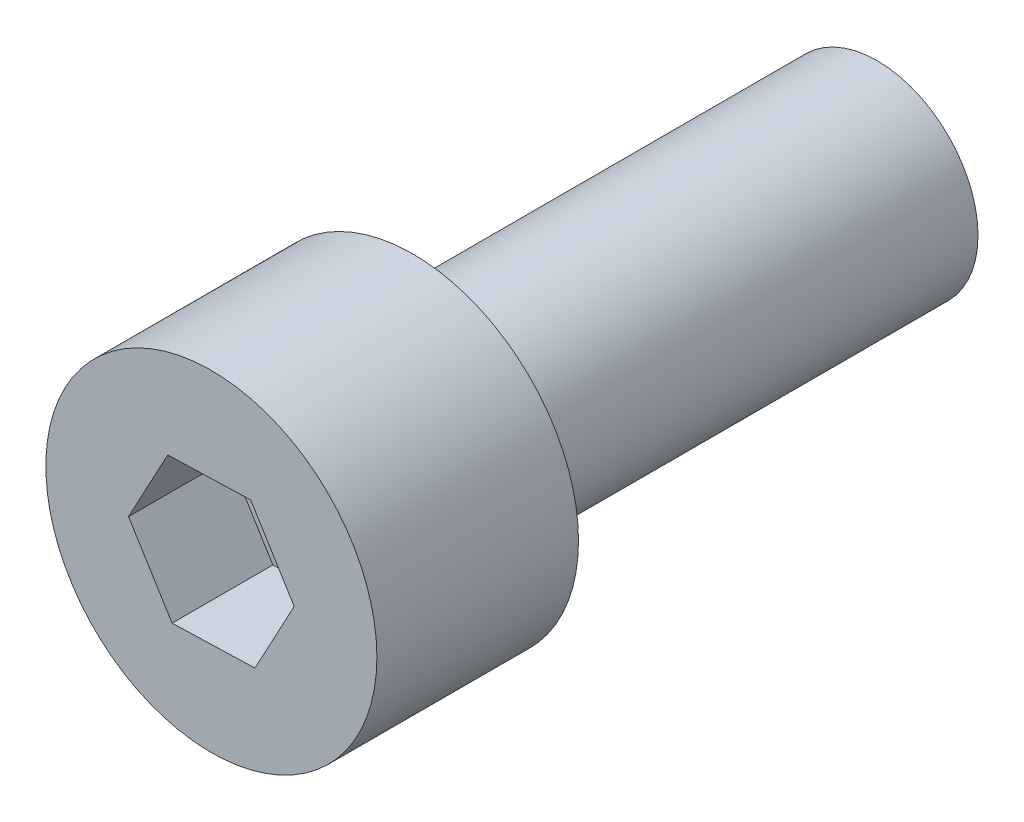
SolidWorks part; units mm, degrees
material "AISI Type A2 Tool Steel"
ref_plane "Front" through (0, 0, 0) normal (0, 0, 1) x (1, 0, 0)
ref_plane "Top" through (0, 0, 0) normal (0, 1, 0) x (1, 0, 0)
ref_plane "Right" through (0, 0, 0) normal (1, 0, 0) x (0, 0, -1)
sketch "Sketch1" plane through (0, 0, 0) normal (0, 0, 1) x (1, 0, 0)
  circle A0 centre (0, 0) radius 2.413
  dimension "D1" = 4.826
extrude "Boss-Extrude1" add sketch "Sketch1" along normal blind 11.1125
cosmetic thread "Cosmetic Thread1" parameters "D2"=3.8811
sketch "Sketch2" plane through (0, 0, 11.1125) normal (0, 0, 1) x (1, 0, 0)
  circle A0 centre (0, 0) radius 3.9624
  dimension "D1" = 7.9248
extrude "Boss-Extrude2" add sketch "Sketch2" along normal blind 4.826
sketch "Sketch3" plane through (0, 0, 15.9385) normal (0, 0, 1) x (1, 0, 0)
  line L1 (-1.9835, -0.0597) -> (-0.94, -1.7476)
  line L2 (-0.94, -1.7476) -> (1.0434, -1.6879)
  line L3 (1.0434, -1.6879) -> (1.9835, 0.0597)
  line L4 (1.9835, 0.0597) -> (0.94, 1.7476)
  line L5 (0.94, 1.7476) -> (-1.0434, 1.6879)
  line L6 (-1.0434, 1.6879) -> (-1.9835, -0.0597)
  circle A0 centre (0, 0) radius 1.9844
  circle A1 centre (0, 0) radius 1.7185 construction
  dimension "D1" = 3.9688
extrude "Cut-Extrude1" cut sketch "Sketch3" against normal blind 2.413 contours L5 L6 L1 L2 L3 L4
